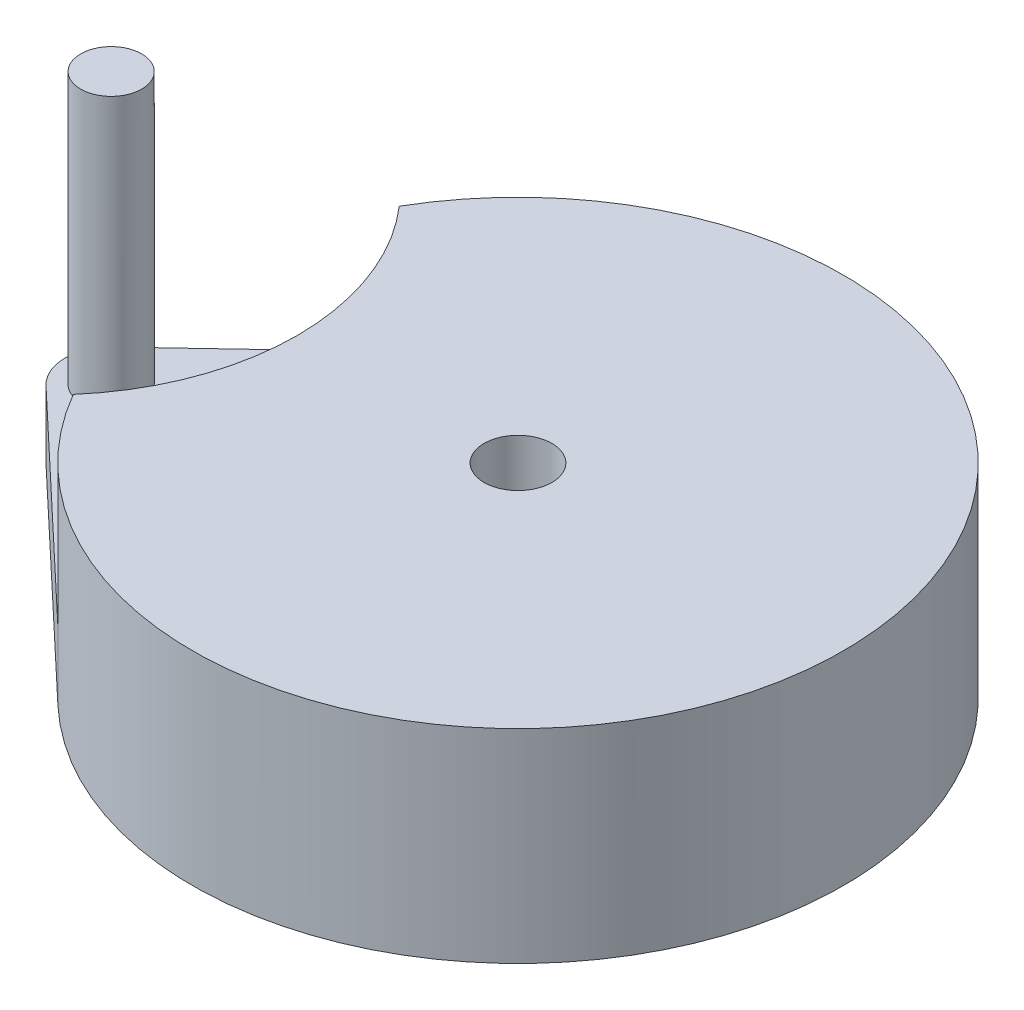
SolidWorks part; units mm, degrees
ref_plane "前基準面" through (0, 0, 0) normal (0, 0, 1) x (1, 0, 0)
ref_plane "上基準面" through (0, 0, 0) normal (0, 1, 0) x (1, 0, 0)
ref_plane "右基準面" through (0, 0, 0) normal (1, 0, 0) x (0, 0, -1)
sketch "草圖2" plane through (0, 0, 0) normal (0, 1, 0) x (1, 0, 0)
  line L0 (-32.3347, 2.4717) -> (-16.48, 17.4473)
  line L1 (-38.1899, 0) -> (38.1899, 0) construction
  line L2 (-32.3347, -2.4717) -> (-16.48, -17.4473)
  circle A1 centre (0, 0) radius 2.5
  arc A2 (-32.3347, 2.4717) -> (-32.3347, -2.4717) centre (-30, 0) ccw
  arc A3 (-16.48, -17.4473) -> (-16.48, 17.4473) centre (0, 0) ccw
  circle A4 centre (-30, 0) radius 2.25 construction
  point P1 (0, 0)
  point P5 (0, 0)
  point P6 (0, -8.9781)
  point P13 (0, 0)
  point P14 (0, 0)
  point P16 (0, 0)
  point P17 (-36.5462, 12.2249)
  point P18 (-30.9054, 0.6887)
  point P19 (0, 0)
  point P20 (0.8293, 0)
  dimension "D1" = 4.5
  dimension "D2" = 5
  dimension "D3" = 3.4
  dimension "D4" = 24
  dimension "D6" = 30
extrude "填料-伸長1" add sketch "草圖2" along normal blind 5
sketch "草圖5" plane through (0, 5, 0) normal (0, 1, 0) x (1, 0, 0)
  line L0 (-23.1074, 0) -> (30.3139, 0) construction
  line L1 (1.9361, 21.5881) -> (1.9361, -21.7622) construction
  arc A0 (-20.7733, -12.0195) -> (-20.7733, 12.0195) centre (0, 0) ccw
  arc A1 (-20.7733, -12.0195) -> (-20.7733, 12.0195) centre (-34.5925, 0) ccw
  circle A2 centre (-30, 0) radius 2.25
  circle A4 centre (0, 0) radius 2.5 construction
  circle A5 centre (0, 0) radius 2.5
  point P11 (0, 0)
  point P12 (0, 0)
  point P13 (0, 0)
  point P15 (0, 0)
  dimension "D1" = 24
  dimension "D2" = 18.315
  dimension "D3" = 4.5
  dimension "D4" = 30
  dimension "D5" = 34.5925
extrude "填料-伸長4" add sketch "草圖5" along normal blind 10
sketch "草圖6" plane through (0, 15, 0) normal (0, 1, 0) x (1, 0, 0)
  circle A1 centre (-30, 0) radius 2.25
  circle A2 centre (-30, 0) radius 2.25
  dimension "D1" = 0
extrude "填料-伸長5" add sketch "草圖6" along normal blind 10
